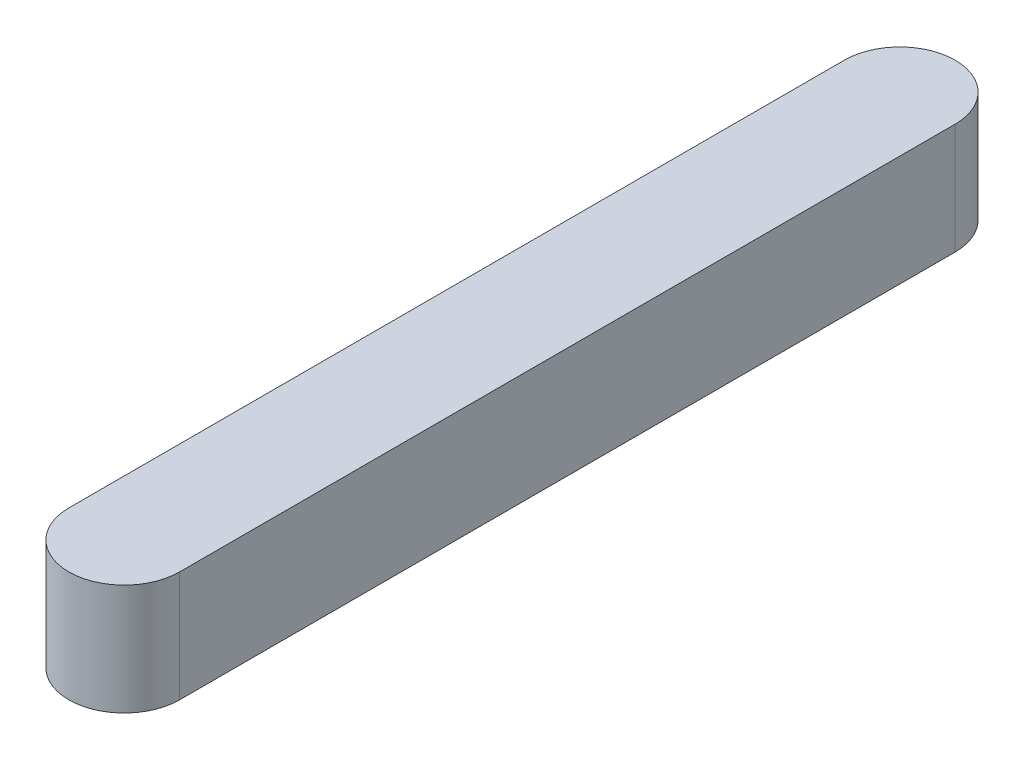
SolidWorks part; units mm, degrees
ref_plane "Front Plane" through (0, 0, 0) normal (0, 0, 1) x (1, 0, 0)
ref_plane "Top Plane" through (0, 0, 0) normal (0, 1, 0) x (1, 0, 0)
ref_plane "Right Plane" through (0, 0, 0) normal (1, 0, 0) x (0, 0, -1)
sketch "Sketch1" plane through (0, 0, 0) normal (1, 0, 0) x (0, 0, -1)
  line L0 (-20, 2.5) -> (-20, -2.5) construction
  line L1 (-20, 2.5) -> (20, 2.5) construction
  line L3 (0, 1.1) -> (0, -1.1) construction
  line L4 (1.1, 0) -> (-1.1, 0) construction
  point P0 (-20, 0)
  point P4 (0, 2.5)
  dimension "Height" = 5
  dimension "Length" = 40
sketch "Sketch3" plane through (0, 0, 0) normal (0, 1, 0) x (1, 0, 0)
  line L0 (0, -17.5) -> (0, 17.5) construction
  line L1 (-2.5, -17.5) -> (-2.5, 17.5)
  line L2 (2.5, -17.5) -> (2.5, 17.5)
  line L3 (-1.1, 0) -> (1.1, 0) construction
  arc A0 (-2.5, -17.5) -> (2.5, -17.5) centre (0, -17.5) ccw
  arc A1 (2.5, 17.5) -> (-2.5, 17.5) centre (0, 17.5) ccw
  point P3 (0, 0)
  point P8 (-2.5, 12.5)
  point P12 (2.5, -12.5)
  dimension "Width" = 5
  dimension "D1" = 7.5
  dimension "D2" = 7.5
sketch "Sketch4" plane through (0, 0, 0) normal (0, 1, 0) x (1, 0, 0)
  line L0 (-2.5, -17.5) -> (-2.5, 17.5) construction
  line L1 (2.5, -17.5) -> (2.5, 17.5) construction
  line L2 (-2.5, -17.5) -> (-2.5, 17.5)
  line L3 (2.5, -17.5) -> (2.5, 17.5)
  arc A0 (2.5, 17.5) -> (-2.5, 17.5) centre (0, 17.5) ccw construction
  arc A1 (-2.5, -17.5) -> (2.5, -17.5) centre (0, -17.5) ccw construction
  arc A2 (2.5, 17.5) -> (-2.5, 17.5) centre (0, 17.5) ccw
  arc A3 (-2.5, -17.5) -> (2.5, -17.5) centre (0, -17.5) ccw
extrude "Boss-Extrude1" add sketch "Sketch4" against normal up to vertex (2.5 mm away) from vertex at 2.5 starting at point (0, 2.5, 20)
equation "\"D1@Sketch3\"=\"Width@Sketch3\"*1.5"
equation "\"D2@Sketch3\"=\"D1@Sketch3\""
